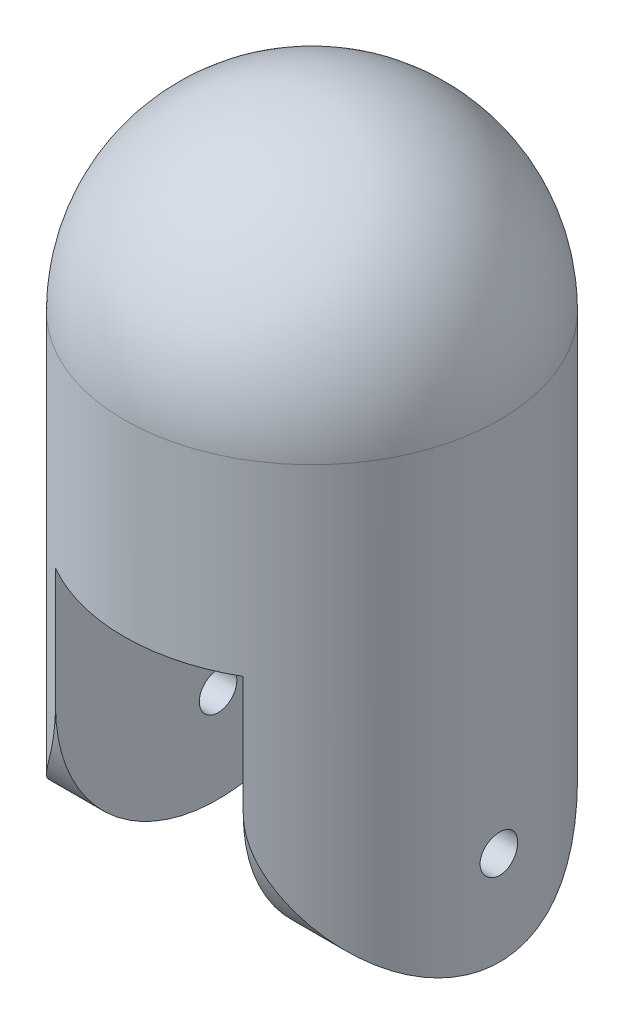
SolidWorks part; units mm, degrees
ref_plane "Front Plane" through (0, 0, 0) normal (0, 0, 1) x (1, 0, 0)
ref_plane "Top Plane" through (0, 0, 0) normal (0, 1, 0) x (1, 0, 0)
ref_plane "Right Plane" through (0, 0, 0) normal (1, 0, 0) x (0, 0, -1)
sketch "Sketch1" plane through (0, 0, 0) normal (0, 1, 0) x (1, 0, 0)
  circle A0 centre (0, 0) radius 5
  dimension "D1" = 10
extrude "Boss-Extrude1" add sketch "Sketch1" against normal blind 5
sketch "Sketch2" plane through (0, -5, 0) normal (0, -1, 0) x (1, 0, 0)
  line L0 (-2.5, 4.3301) -> (-2.5, -4.3301)
  line L1 (0, -2.75) -> (0, 2.75) construction
  line L2 (2.5, 4.3301) -> (2.5, -4.3301)
  circle A0 centre (0, 0) radius 5 construction
  arc A1 (-2.5, 4.3301) -> (-2.5, -4.3301) centre (0, 0) ccw
  arc A2 (2.5, 4.3301) -> (2.5, -4.3301) centre (0, 0) cw
  dimension "D1" = 2.5
extrude "Boss-Extrude3" add sketch "Sketch2" along normal blind 7.5
sketch "Sketch3" plane through (-2.5, 0, 0) normal (1, 0, 0) x (0, 0, -1)
  line L0 (4.3301, -12.5) -> (4.3301, -5) construction
  line L1 (4.3301, -12.5) -> (-4.3301, -12.5) construction
  line L2 (-4.3301, -12.5) -> (-4.3301, -5) construction
  line L3 (4.3301, -8.1699) -> (5.6828, -8.1699)
  line L4 (5.6828, -8.1699) -> (5.6828, -17.3354)
  line L5 (5.6828, -17.3354) -> (-5.1988, -17.3354)
  line L6 (-5.1988, -17.3354) -> (-5.1988, -8.1699)
  line L7 (-5.1988, -8.1699) -> (-4.3301, -8.1699)
  arc A0 (0, -12.5) -> (4.3301, -8.1699) centre (0, -8.1699) ccw
  arc A1 (0, -12.5) -> (-4.3301, -8.1699) centre (0, -8.1699) cw
  point P0 (0, -8.1699)
  dimension "D1" = 4.3301
  dimension "D2" = 4.3301
  dimension "D3" = 10.8816
  dimension "D4" = 9.1656
  dimension "D5" = 0.8686
  dimension "D6" = 1.3527
extrude "Cut-Extrude3" cut sketch "Sketch3" against normal blind 7.5 and the other way blind 7.5
sketch "Sketch4" plane through (2.5, 0, 0) normal (-1, 0, 0) x (0, 0, 1)
  line L0 (-4.3301, -8.1699) -> (-4.3301, -5) construction
  line L1 (4.3301, -5) -> (-4.3301, -5) construction
  point P0 (0, -10)
  point P3 (0, 0)
  dimension "D1" = 4.3301
  dimension "D2" = 5
hole_wizard "#95 (0.03937008) Diameter Hole1" positions "3DSketch1" profile "Sketch5" hole size "#95" standard "ANSI Inch"
sketch3d "3DSketch1"
  point P0 (2.5, -10, 0)
sketch "Sketch5" plane through (2.5, -10, 0) normal (0, 1, 0) x (0, 0, 1)
  line L0 (0, 0) -> (0, 2.5)
  line L1 (0, 2.5) -> (0.5, 2.5)
  line L2 (0.5, 2.5) -> (0.5, 0)
  line L5 (0.5, 0) -> (0, 0)
  line L11 (0, -6.35) -> (0, 107.95) construction
  dimension "Thru Hole Dia." = 1
  dimension "Thru Hole Depth" = 2.5
hole_wizard "#94 (0.03937008) Diameter Hole1" positions "3DSketch2" profile "Sketch6" hole size "#94" standard "ANSI Inch" end condition through all
sketch3d "3DSketch2"
  point P0 (2.5, -10, 0)
sketch "Sketch6" plane through (2.5, -10, 0) normal (0, 1, 0) x (0, 0, -1)
  line L0 (0, 0) -> (0, 7.5)
  line L1 (0, 7.5) -> (0.5, 7.5)
  line L2 (0.5, 7.5) -> (0.5, 0)
  line L5 (0.5, 0) -> (0, 0)
  line L11 (0, -6.35) -> (0, 107.95) construction
  dimension "Thru Hole Dia." = 1
  dimension "Thru Hole Depth" = 7.5
sketch "Sketch7" plane through (0, 0, 0) normal (0, 0, 1) x (1, 0, 0)
  line L0 (0, 0) -> (0, 5)
  line L1 (0, 0) -> (-5, 0)
  arc A0 (-5, 0) -> (0, 5) centre (0, 0) cw
  point P3 (-19.9388, -1.7122)
  dimension "D1" = 5
revolve "Revolve1" add sketch "Sketch7" angle 360 about L0
